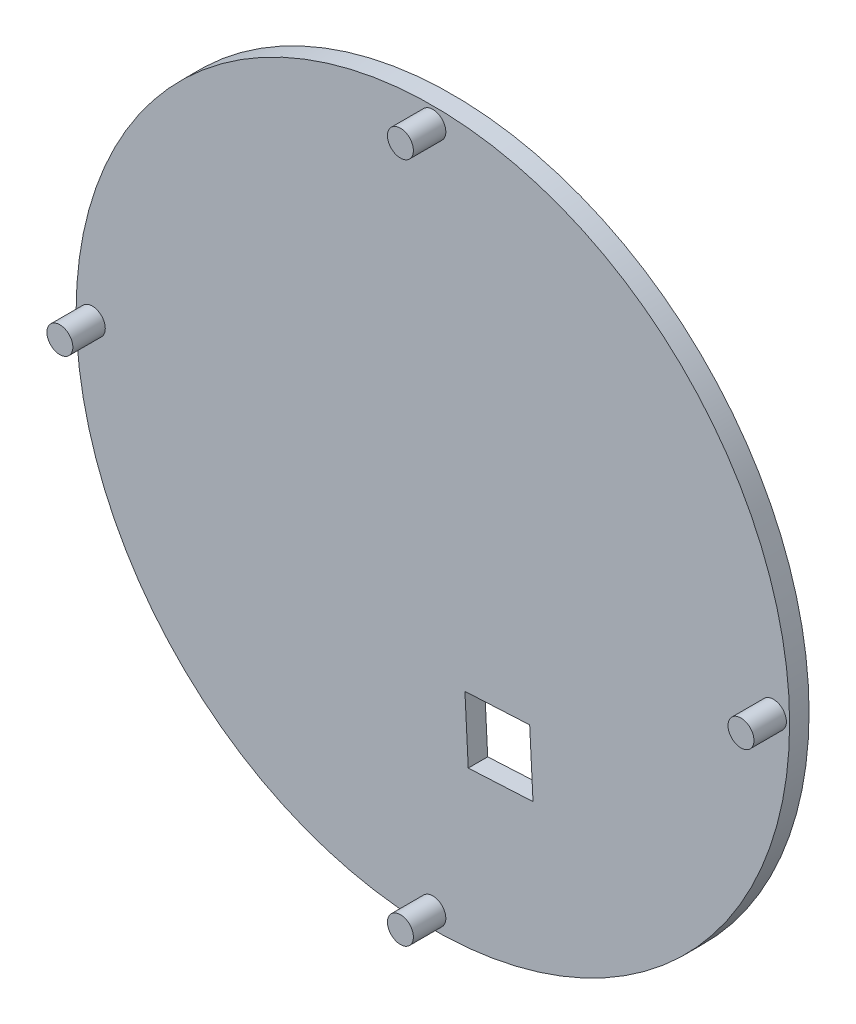
SolidWorks part; units mm, degrees
ref_plane "Ön Düzlem" through (0, 0, 0) normal (0, 0, 1) x (1, 0, 0)
ref_plane "Üst Düzlem" through (0, 0, 0) normal (0, 1, 0) x (1, 0, 0)
ref_plane "Sağ Düzlem" through (0, 0, 0) normal (1, 0, 0) x (0, 0, -1)
sketch "Sketch1" plane through (0, 0, 0) normal (0, 0, 1) x (1, 0, 0)
  circle A0 centre (0, 0) radius 55
  dimension "D1" = 110
extrude "Boss-Extrude1" add sketch "Sketch1" along normal blind 3
sketch "Sketch2" plane through (0, 0, 3) normal (0, 0, 1) x (1, 0, 0)
  circle A1 centre (0, 52.5021) radius 2
  circle A2 centre (52.5021, 0) radius 2
  circle A3 centre (0, -52.5021) radius 2
  circle A4 centre (-52.5021, 0) radius 2
  dimension "D2" = 4
extrude "Boss-Extrude2" add sketch "Sketch2" along normal blind 5
sketch "Sketch5" plane through (0, 0, 0) normal (0, 0, -1) x (-1, 0, 0)
  line L0 (-2, 3.4254) -> (-2, 8.4254)
  line L1 (2, 8.4254) -> (2, 3.4254)
  line L2 (2, 3.4254) -> (15.9261, 1.9885)
  line L3 (15.9575, -1.985) -> (2, -3.0746)
  line L4 (2, -3.0746) -> (2, -8.5746)
  line L5 (-2, -8.5746) -> (-2, -3.5746)
  line L6 (-2, -3.5746) -> (-18.9131, -1.8744)
  line L7 (-18.9131, 2.1051) -> (-2, 3.4254)
  arc A0 (-2, 8.4254) -> (2, 8.4254) centre (0, 8.4254) cw
  arc A1 (15.9261, 1.9885) -> (15.9575, -1.985) centre (15.7209, 0) cw
  arc A2 (2, -8.5746) -> (-2, -8.5746) centre (0, -8.5746) cw
  arc A3 (-18.9131, -1.8744) -> (-18.9131, 2.1051) centre (-18.7131, 0.1153) cw
  point P16 (0, 0)
extrude "Cut-Extrude2" cut sketch "Sketch5" against normal blind 1.5
sketch "Sketch7" plane through (0, 0, 0) normal (0, 0, -1) x (-1, 0, 0)
  line L0 (-14.9276, -20.21) -> (-15.4416, -30.1968)
  line L1 (-14.9276, -20.21) -> (-4.9408, -20.724)
  line L2 (-4.9408, -20.724) -> (-5.4548, -30.7108)
  line L3 (-5.4548, -30.7108) -> (-15.4416, -30.1968)
extrude "Cut-Extrude3" cut sketch "Sketch7" against normal blind 23.5
